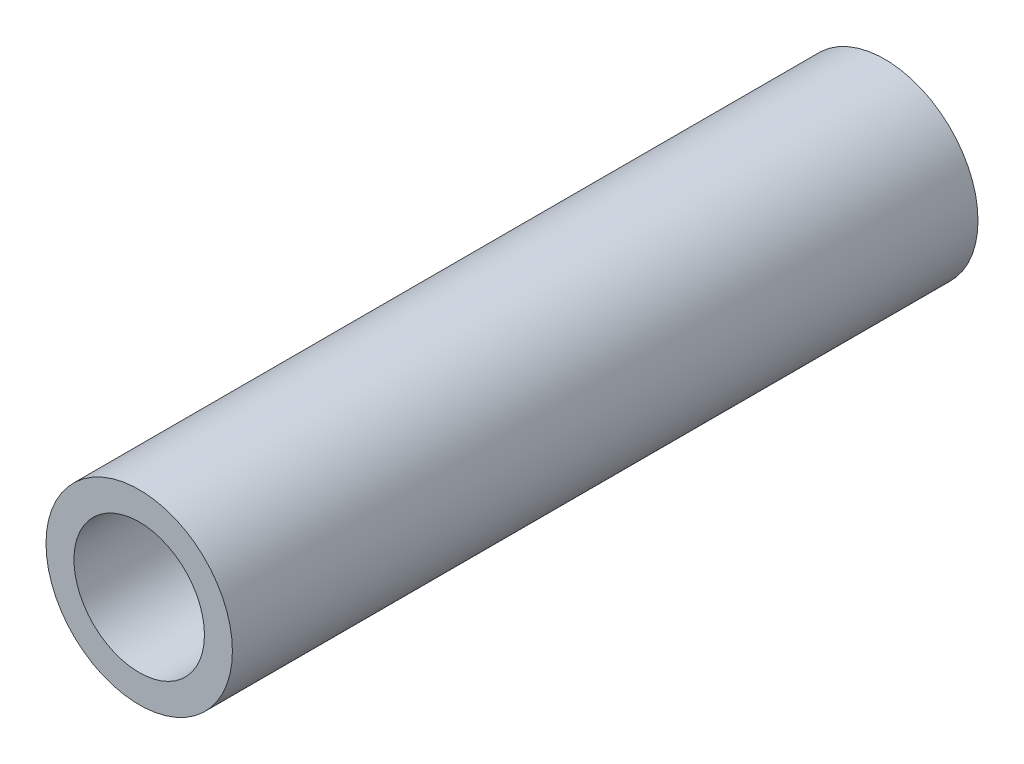
SolidWorks part; units mm, degrees
ref_plane "前视基准面" through (0, 0, 0) normal (0, 0, 1) x (1, 0, 0)
ref_plane "上视基准面" through (0, 0, 0) normal (0, 1, 0) x (1, 0, 0)
ref_plane "右视基准面" through (0, 0, 0) normal (1, 0, 0) x (0, 0, -1)
other "Configuration Table"
sketch "草图1" plane through (0, 0, 0) normal (0, 0, 1) x (1, 0, 0)
  circle A1 centre (0, 0) radius 2
  circle A2 centre (0, 0) radius 1.4
  dimension "D1" = 4
  dimension "D2" = 2.8
extrude "凸台-拉伸1" add sketch "草图1" along normal blind 16
